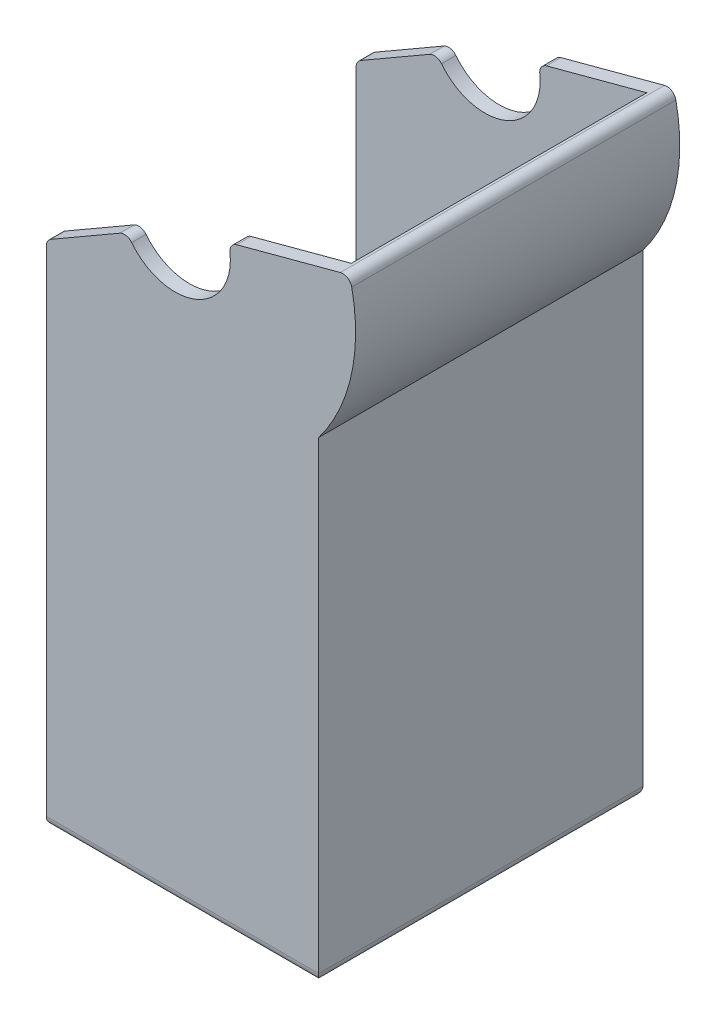
SolidWorks part; units mm, degrees
ref_plane "Front Plane" through (0, 0, 0) normal (0, 0, 1) x (1, 0, 0)
ref_plane "Top Plane" through (0, 0, 0) normal (0, 1, 0) x (1, 0, 0)
ref_plane "Right Plane" through (0, 0, 0) normal (1, 0, 0) x (0, 0, -1)
sketch "Sketch1" plane through (0, 0, 0) normal (0, 0, 1) x (1, 0, 0)
  circle A0 centre (0, 0) radius 49
  dimension "D1" = 98
extrude "Boss-Extrude1" add sketch "Sketch1" along normal blind 88
sketch "Sketch2" plane through (0, 0, 0) normal (0, 0, -1) x (-1, 0, 0)
  line L0 (0, 0) -> (-47.3304, 12.6821)
  line L1 (0, 0) -> (42.4352, -24.5)
  line L2 (0, 0) -> (0, -49) construction
  circle A0 centre (0, 0) radius 49 construction
  arc A1 (-47.3304, 12.6821) -> (42.4352, -24.5) centre (0, 0) cw
  dimension "D1" = 105
  dimension "D2" = 60
extrude "Cut-Extrude1" cut sketch "Sketch2" against normal up to surface (88 mm away) up to face at (49, 0, 88)
sketch "Sketch3" plane through (0, 0, 0) normal (0, 0, -1) x (-1, 0, 0)
  line L1 (-38.97, -158.24) -> (38.97, -158.24)
  line L2 (-38.97, -158.24) -> (-38.97, -29.7042)
  line L3 (-38.97, -29.7042) -> (38.97, -29.7042)
  line L4 (38.97, -158.24) -> (38.97, -29.7042)
  line L5 (-38.97, -158.24) -> (38.97, -29.7042) construction
  line L6 (-38.97, -29.7042) -> (38.97, -158.24) construction
  arc A0 (-47.3304, 12.6821) -> (42.4352, -24.5) centre (0, 0) ccw construction
  point P0 (0, -93.9721)
  dimension "D1" = 158.24
  dimension "D2" = 77.94
extrude "Boss-Extrude2" add sketch "Sketch3" against normal up to surface (88 mm away) up to face at (7.0663, -17.0597, 88)
ref_plane "Plane1" through (0, 0, 44) normal (0, 0, -1) x (-1, 0, 0)
sketch "Sketch4" plane through (0, 0, 44) normal (0, 0, -1) x (-1, 0, 0)
  circle A0 centre (0, 0) radius 45.5
  dimension "D1" = 91
extrude "Cut-Extrude2" cut sketch "Sketch4" along normal offset from surface 3.9 and the other way offset from surface (40.1 mm away) 3.9 up to face at (1.3908, -55.5332, 0) other way up to face at (1.3908, -55.5332, 88)
sketch "Sketch5" plane through (0, 0, 44) normal (0, 0, -1) x (-1, 0, 0)
  line L0 (-38.97, -158.24) -> (38.97, -158.24) construction
  line L1 (-34.97, 0) -> (34.97, 0)
  line L2 (-34.97, 0) -> (-34.97, -158.24)
  line L3 (-34.97, -158.24) -> (34.97, -158.24)
  line L4 (34.97, 0) -> (34.97, -158.24)
  line L5 (-34.97, 0) -> (34.97, -158.24) construction
  line L6 (-34.97, -158.24) -> (34.97, 0) construction
  point P0 (0, -79.12)
  dimension "D1" = 69.94
extrude "Cut-Extrude3" cut sketch "Sketch5" along normal offset from surface 3.9 and the other way offset from surface (40.1 mm away) 3.9 up to face at (1.3908, -55.5332, 0) other way up to face at (1.3908, -55.5332, 88)
sketch "Sketch6" plane through (-38.97, 0, 0) normal (-1, 0, 0) x (0, 0, 1)
  line L0 (44, 50.2894) -> (44, -50.2894) construction
  line L1 (0, 11.7763) -> (88, 11.7763)
  line L2 (0, 11.7763) -> (0, -158.2692)
  line L3 (0, -158.2692) -> (88, -158.2692)
  line L4 (88, 11.7763) -> (88, -158.2692)
  line L5 (0, 11.7763) -> (88, -158.2692) construction
  line L6 (0, -158.2692) -> (88, 11.7763) construction
  line L7 (84.1, 11.7763) -> (3.9, 11.7763) construction
  line L8 (88, -158.24) -> (88, -29.7042) construction
  point P0 (44, -73.2465)
extrude "Cut-Extrude5" cut sketch "Sketch6" along normal through all and the other way blind 4
sketch "Sketch7" plane through (0, 0, 0) normal (0, 0, -1) x (-1, 0, 0)
  circle A0 centre (0, 0) radius 15
  dimension "D1" = 30
extrude "Cut-Extrude6" cut sketch "Sketch7" against normal through all
fillet "Fillet1" radius 2.5 10 edges at (2, -158.24, 88) (2, -158.24, 0) (38.97, -158.24, 44) (47.3304, 12.6821, 44) (14.4889, 3.8823, 86.05) (-12.9904, -7.5, 86.05) (-34.97, -20.1899, 86.05) (-34.97, -20.1899, 1.95) (-12.9904, -7.5, 1.95) (14.4889, 3.8823, 1.95)
